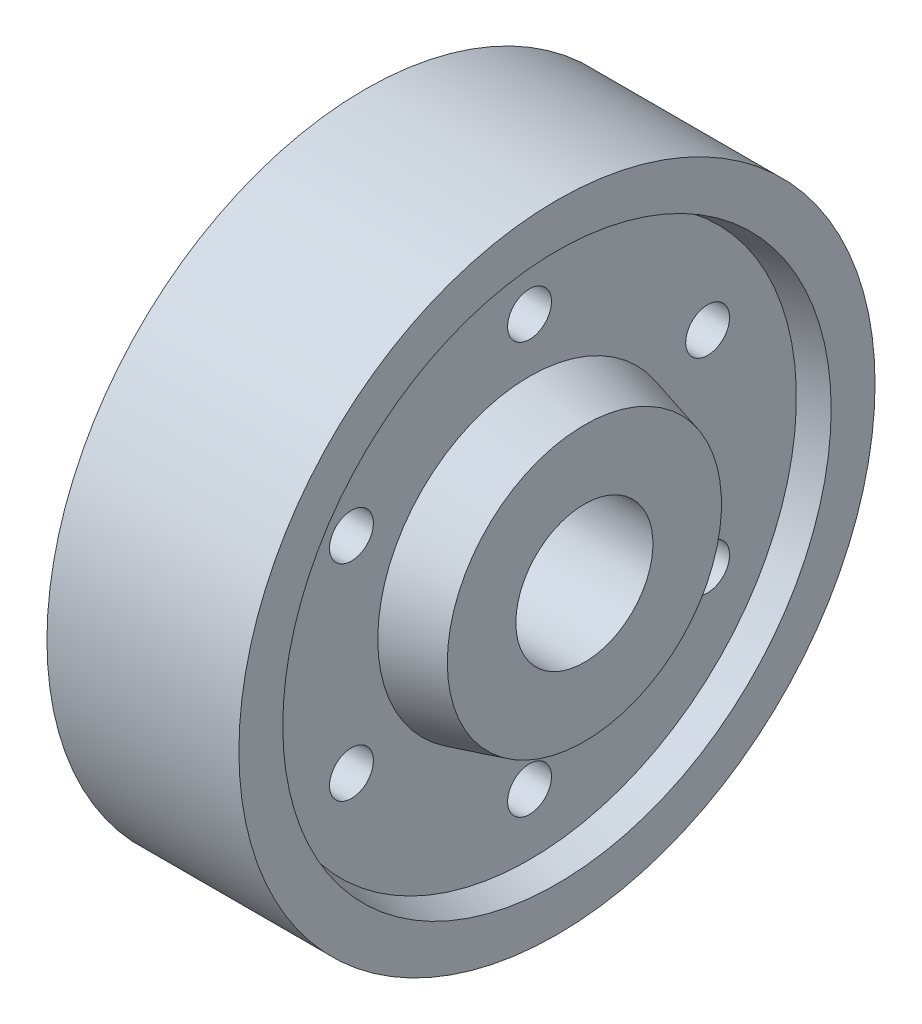
SolidWorks part; units mm, degrees
ref_plane "Front Plane" through (0, 0, 0) normal (0, 0, 1) x (1, 0, 0)
ref_plane "Top Plane" through (0, 0, 0) normal (0, 1, 0) x (1, 0, 0)
ref_plane "Right Plane" through (0, 0, 0) normal (1, 0, 0) x (0, 0, -1)
sketch "Sketch1" plane through (0, 0, 0) normal (0, 1, 0) x (1, 0, 0)
  line L0 (0, 0) -> (59.9806, 0) construction
  line L1 (45, 25) -> (35, 27.6795)
  line L2 (0, 12.5) -> (0, 25)
  line L3 (0, 25) -> (10, 27.6795)
  line L4 (10, 27.6795) -> (10, 48.6603)
  line L5 (5, 26.3397) -> (5, 58)
  line L6 (5, 58) -> (40, 58)
  line L7 (10, 48.6603) -> (5, 50)
  line L8 (22.5, 58) -> (22.5, -7.2674) construction
  line L9 (35, 48.6603) -> (40, 50)
  line L10 (40, 26.3397) -> (40, 58)
  line L11 (35, 27.6795) -> (35, 48.6603)
  line L12 (0, 12.5) -> (45, 12.5)
  line L13 (45, 12.5) -> (45, 25)
  point P10 (5, 37.5)
  point P13 (49.5155, 37.5)
  point P14 (5, 33.5)
  point P15 (49.5155, 33.5)
  point P16 (5, 41.5)
  point P17 (49.5155, 41.5)
  point P21 (22.5, 12.5)
  dimension "D1" = 12.5
  dimension "D2" = 12.5
  dimension "D3" = 105
  dimension "D4" = 10
  dimension "D5" = 17.5
  dimension "D6" = 105
  dimension "D7" = 50
  dimension "D8" = 58
  dimension "D9" = 37.5
revolve "Revolve2" add sketch "Sketch1" angle 360 about L0
sketch "Sketch5" plane through (45, 0, 0) normal (1, 0, 0) x (0, 0, -1)
  circle A0 centre (0, 0) radius 37.5 construction
  circle A1 centre (0, 37.5) radius 4
  circle A2 centre (32.476, 18.75) radius 4
  circle A3 centre (32.476, -18.75) radius 4
  circle A4 centre (0, -37.5) radius 4
  circle A5 centre (-32.476, -18.75) radius 4
  circle A6 centre (-32.476, 18.75) radius 4
  point P18 (0, 0)
  dimension "D1" = 75
  dimension "D2" = 8
  dimension "D3" = 6
extrude "Cut-Extrude1" cut sketch "Sketch5" against normal blind 35
